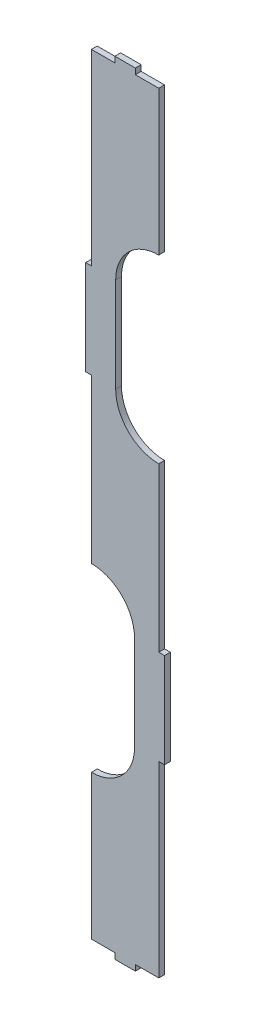
SolidWorks part; units mm, degrees
ref_plane "Front Plane" through (0, 0, 0) normal (0, 0, 1) x (1, 0, 0)
ref_plane "Top Plane" through (0, 0, 0) normal (0, 1, 0) x (1, 0, 0)
ref_plane "Right Plane" through (0, 0, 0) normal (1, 0, 0) x (0, 0, -1)
sketch "Sketch2" plane through (0, 0, 0) normal (0, 0, 1) x (1, 0, 0)
  line L0 (0, 286) -> (0, -286) construction
  line L1 (-25, -286) -> (-7.6, -286)
  line L2 (-25, -286) -> (-25, -178.7666)
  line L3 (-25, 286) -> (-7.6, 286)
  line L4 (25, -286) -> (25, -146.7666)
  line L5 (-25, -286) -> (25, 286) construction
  line L6 (-25, 286) -> (25, -286) construction
  line L7 (25, 0) -> (-25, 0) construction
  line L8 (-25, 146.7667) -> (-25, 286)
  line L9 (-25, 146.7667) -> (-29.3, 146.7667)
  line L11 (-25, 76.5667) -> (-29.3, 76.5667)
  line L12 (-29.3, 146.7667) -> (-29.3, 76.5667)
  line L13 (-25, -44.5666) -> (-25, 76.5667)
  line L18 (29.3, -76.5666) -> (29.3, -146.7666)
  line L19 (25, -146.7666) -> (29.3, -146.7666)
  line L20 (25, -76.5666) -> (29.3, -76.5666)
  line L24 (25, 178.7667) -> (25, 286)
  line L25 (25, -76.5666) -> (25, 44.5667)
  line L26 (7.6, 286) -> (25, 286)
  line L28 (-7.6, 286) -> (-7.6, 290.3)
  line L29 (-7.6, 290.3) -> (7.6, 290.3)
  line L30 (7.6, 286) -> (7.6, 290.3)
  line L31 (7.6, -286) -> (25, -286)
  line L33 (-7.6, -286) -> (-7.6, -290.3)
  line L34 (-7.6, -290.3) -> (7.6, -290.3)
  line L35 (7.6, -286) -> (7.6, -290.3)
  line L37 (-7, 76.5667) -> (-7, 146.7667)
  line L40 (7, -146.7666) -> (7, -76.5666)
  arc A0 (-7, 76.5667) -> (25, 44.5667) centre (25, 76.5667) ccw
  arc A1 (25, 178.7667) -> (-7, 146.7667) centre (25, 146.7667) ccw
  arc A2 (-25, -178.7666) -> (7, -146.7666) centre (-25, -146.7666) ccw
  arc A3 (7, -76.5666) -> (-25, -44.5666) centre (-25, -76.5666) ccw
  point P0 (0, 0)
  point P14 (-29.3, 111.6667)
  point P19 (29.3, -111.6666)
  point P32 (0, 290.3)
  point P38 (0, -290.3)
  dimension "D1" = 572
  dimension "D2" = 50
  dimension "D3" = 4.3
  dimension "D4" = 70.2
  dimension "D5" = 174.3333
  dimension "D6" = 223.3333
  dimension "D7" = 70.2
  dimension "D8" = 4.3
  dimension "D9" = 15.2
  dimension "D10" = 15.2
  dimension "D11" = 4.3
  dimension "D12" = 18
  dimension "D13" = 4.3
  dimension "D14" = 18
  dimension "D15" = 70.2
  dimension "D16" = 174.3334
extrude "Boss-Extrude1" add sketch "Sketch2" along normal blind 4.3
equation "\"4ز3\"=5.6211"
